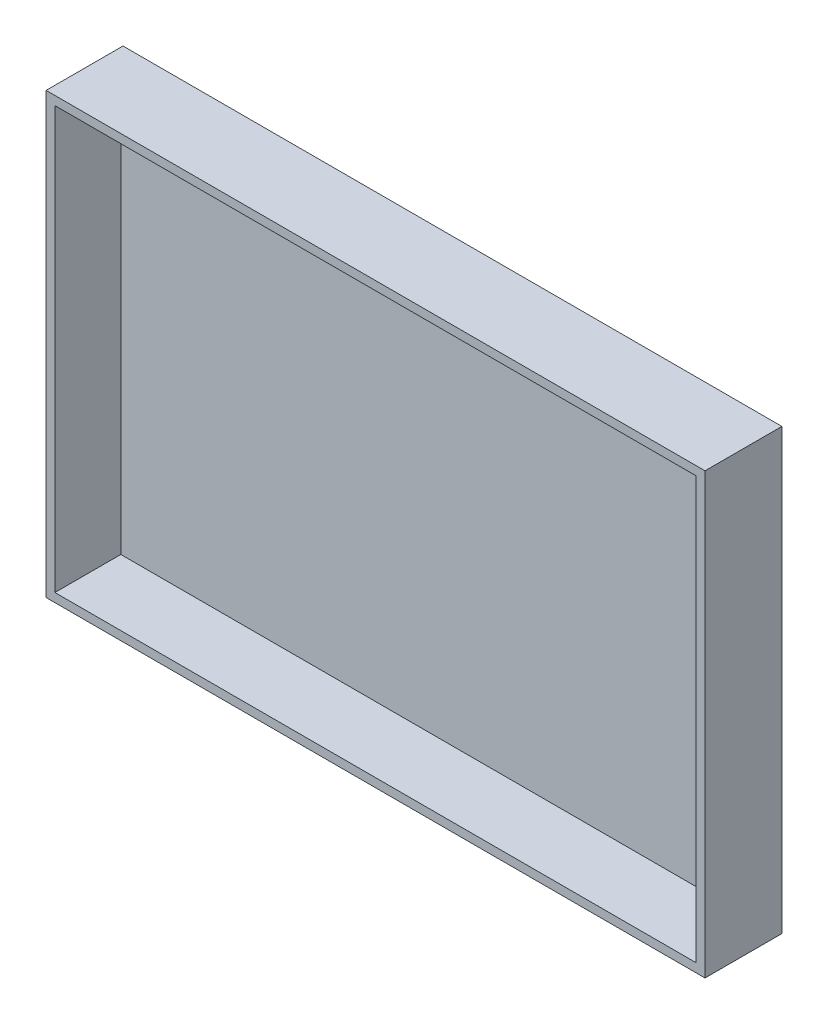
SolidWorks part; units mm, degrees
ref_plane "Plan de face" through (0, 0, 0) normal (0, 0, 1) x (1, 0, 0)
ref_plane "Plan de dessus" through (0, 0, 0) normal (0, 1, 0) x (1, 0, 0)
ref_plane "Plan de droite" through (0, 0, 0) normal (1, 0, 0) x (0, 0, -1)
sketch "Esquisse1" plane through (0, 0, 0) normal (0, 0, 1) x (1, 0, 0)
  line L1 (0, 0) -> (600, 0)
  line L2 (0, 0) -> (0, 400)
  line L3 (0, 400) -> (600, 400)
  line L4 (600, 0) -> (600, 400)
  dimension "D1" = 600
  dimension "D2" = 400
extrude "Boss.-Extru.1" add sketch "Esquisse1" along normal blind 10
sketch "Esquisse2" plane through (0, 0, 10) normal (0, 0, 1) x (1, 0, 0)
  line L0 (8, 392) -> (8, 8)
  line L1 (8, 8) -> (592, 8)
  line L2 (592, 8) -> (592, 392)
  line L3 (592, 392) -> (8, 392)
  line L4 (0, 400) -> (0, 0)
  line L5 (0, 0) -> (600, 0)
  line L6 (600, 0) -> (600, 400)
  line L7 (600, 400) -> (0, 400)
  line L8 (0, 400) -> (0, 0)
  line L9 (0, 0) -> (600, 0)
  line L10 (600, 0) -> (600, 400)
  line L11 (600, 400) -> (0, 400)
  dimension "D1" = 0
  dimension "D2" = 8
extrude "Boss.-Extru.2" add sketch "Esquisse2" along normal blind 60
